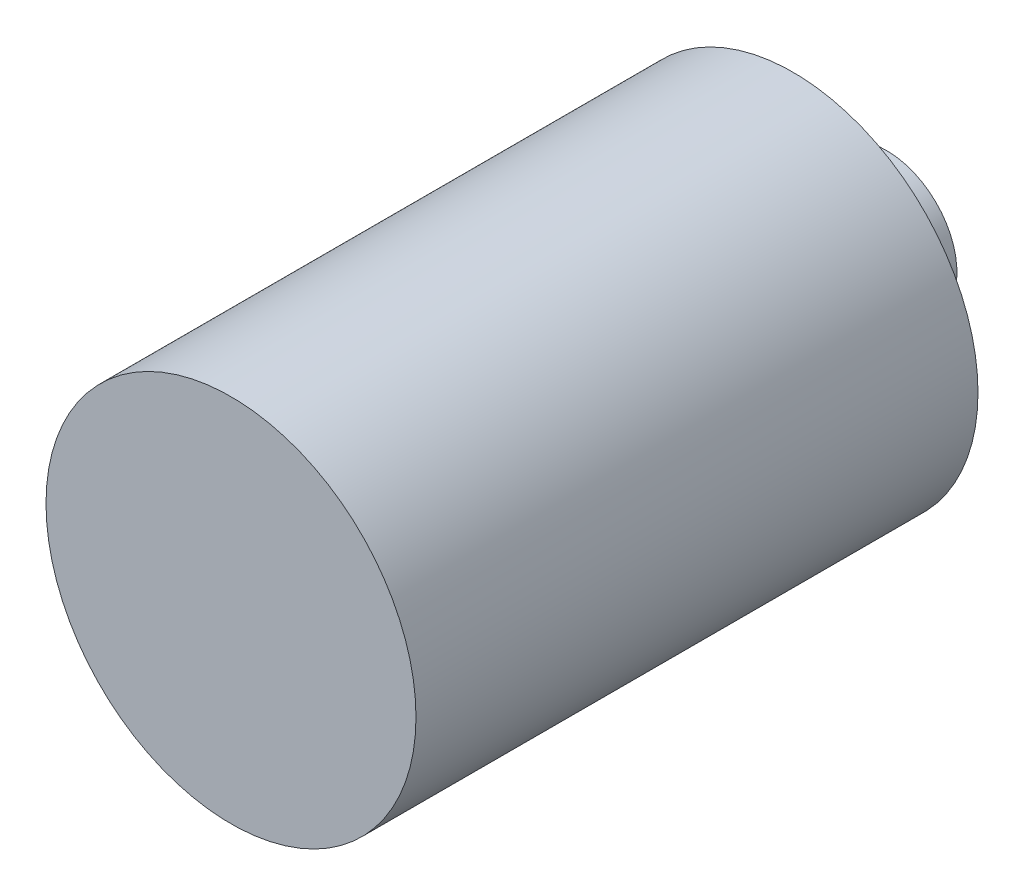
SolidWorks part; units mm, degrees
material "铸造合金钢"
ref_plane "前视基准面" through (0, 0, 0) normal (0, 0, 1) x (1, 0, 0)
ref_plane "上视基准面" through (0, 0, 0) normal (0, 1, 0) x (1, 0, 0)
ref_plane "右视基准面" through (0, 0, 0) normal (1, 0, 0) x (0, 0, -1)
sketch "草图1" plane through (0, 0, 0) normal (0, 0, 1) x (1, 0, 0)
  circle A0 centre (0, 0) radius 3.95
  dimension "D1" = 7.9
extrude "凸台-拉伸1" add sketch "草图1" along normal blind 12
sketch "草图2" plane through (0, 0, 0) normal (0, 0, -1) x (-1, 0, 0)
  circle A0 centre (0, 0) radius 1.5
  dimension "D1" = 3
extrude "凸台-拉伸2" add sketch "草图2" along normal blind 2
